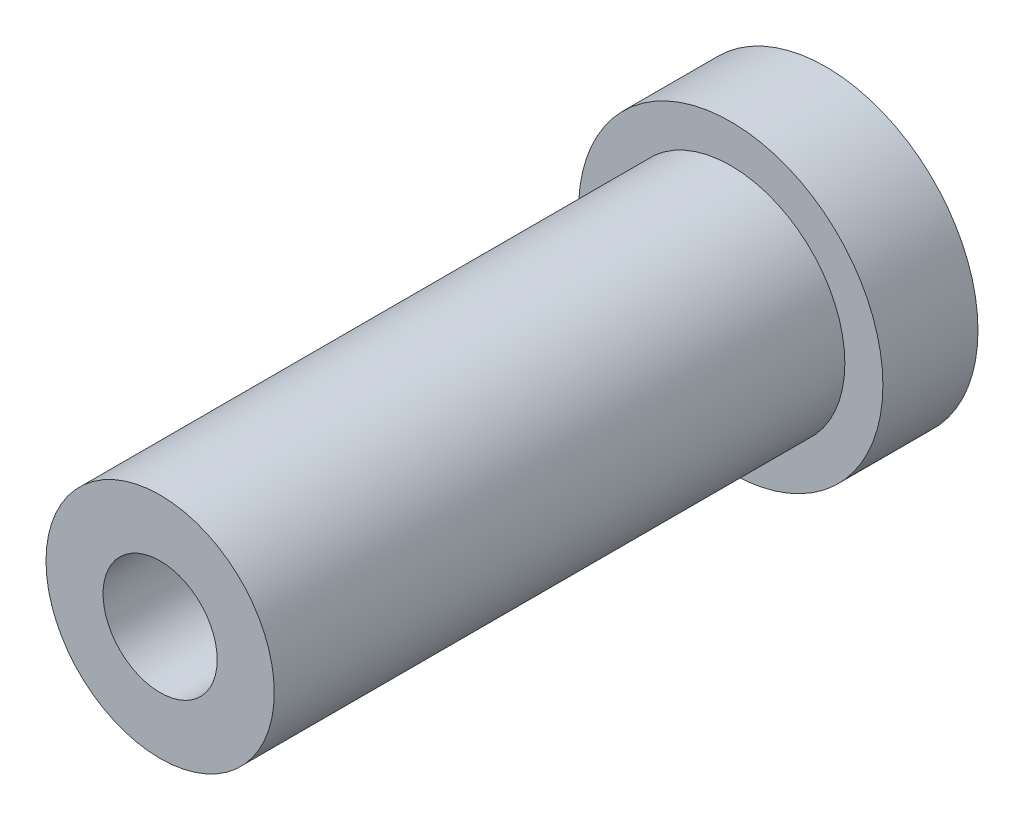
SolidWorks part; units mm, degrees
ref_plane "Front Plane" through (0, 0, 0) normal (0, 0, 1) x (1, 0, 0)
ref_plane "Top Plane" through (0, 0, 0) normal (0, 1, 0) x (1, 0, 0)
ref_plane "Right Plane" through (0, 0, 0) normal (1, 0, 0) x (0, 0, -1)
sketch "Sketch1" plane through (0, 0, 0) normal (0, 0, 1) x (1, 0, 0)
  circle A0 centre (0, 0) radius 4
  dimension "D1" = 8
extrude "Boss-Extrude1" add sketch "Sketch1" along normal blind 2.5
sketch "Sketch4" plane through (0, 0, 2.5) normal (0, 0, 1) x (1, 0, 0)
  circle A0 centre (0, 0) radius 3
extrude "Boss-Extrude2" add sketch "Sketch4" along normal blind 15
sketch "Sketch5" plane through (0, 0, 17.5) normal (0, 0, 1) x (1, 0, 0)
  circle A0 centre (0, 0) radius 1.5
extrude "Cut-Extrude1" cut sketch "Sketch5" against normal blind 15
